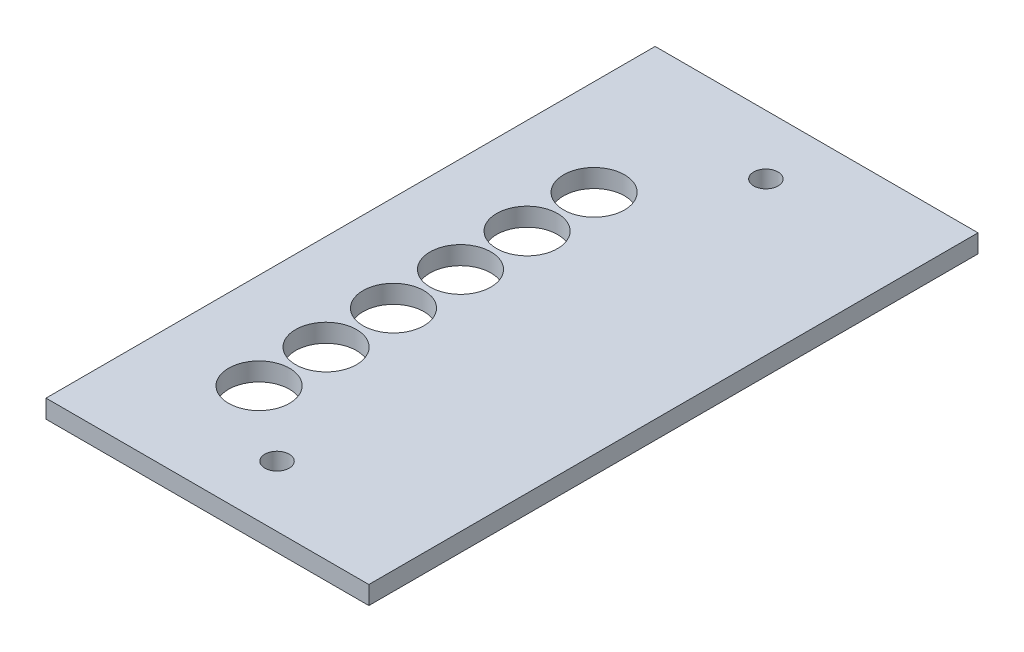
SolidWorks part; units mm, degrees
ref_plane "Plano frontal" through (0, 0, 0) normal (0, 0, 1) x (1, 0, 0)
ref_plane "Plano superior" through (0, 0, 0) normal (0, 1, 0) x (1, 0, 0)
ref_plane "Plano direito" through (0, 0, 0) normal (1, 0, 0) x (0, 0, -1)
sketch "Esboço2" plane through (-2.8029, 0, -5.7587) normal (0, 1, 0) x (1, 0, 0)
  line L1 (-52.9307, 100) -> (0.0693, 100)
  line L2 (-52.9307, 100) -> (-52.9307, 0)
  line L3 (-52.9307, 0) -> (0.0693, 0)
  line L4 (0.0693, 100) -> (0.0693, 0)
extrude "Ressalto-extrusão1" add sketch "Esboço2" along normal blind 3 contours L1 L4 L3 L2
sketch "Esboço4" plane through (0, 3, 0) normal (0, 1, 0) x (1, 0, 0)
  circle A2 centre (-27.8029, 96) radius 2
sketch "Esboço8" plane through (0, 3, 0) normal (0, 1, 0) x (1, 0, 0)
  line L5 (-40, 25) -> (-40, 36) construction
  line L7 (-40, 47.07) -> (-40, 58.07) construction
  line L9 (-40, 69) -> (-40, 80) construction
  circle A0 centre (-40, 25) radius 5
  circle A1 centre (-40, 36) radius 5
  circle A2 centre (-40, 47.07) radius 5
  circle A3 centre (-40, 58.07) radius 5
  circle A4 centre (-40, 69) radius 5
  circle A5 centre (-40, 80) radius 5
  dimension "D3" = 11
  dimension "D5" = 11
  dimension "D7" = 11
sketch "Esboço14" plane through (0, 3, 0) normal (0, 1, 0) x (1, 0, 0)
  circle A0 centre (-27.8029, 15.7587) radius 2
extrude "Corte-extrusão10" cut sketch "Esboço14" against normal blind 10
extrude "Corte-extrusão11" cut sketch "Esboço8" against normal blind 10
extrude "Corte-extrusão12" cut sketch "Esboço4" against normal blind 10 contours A2
